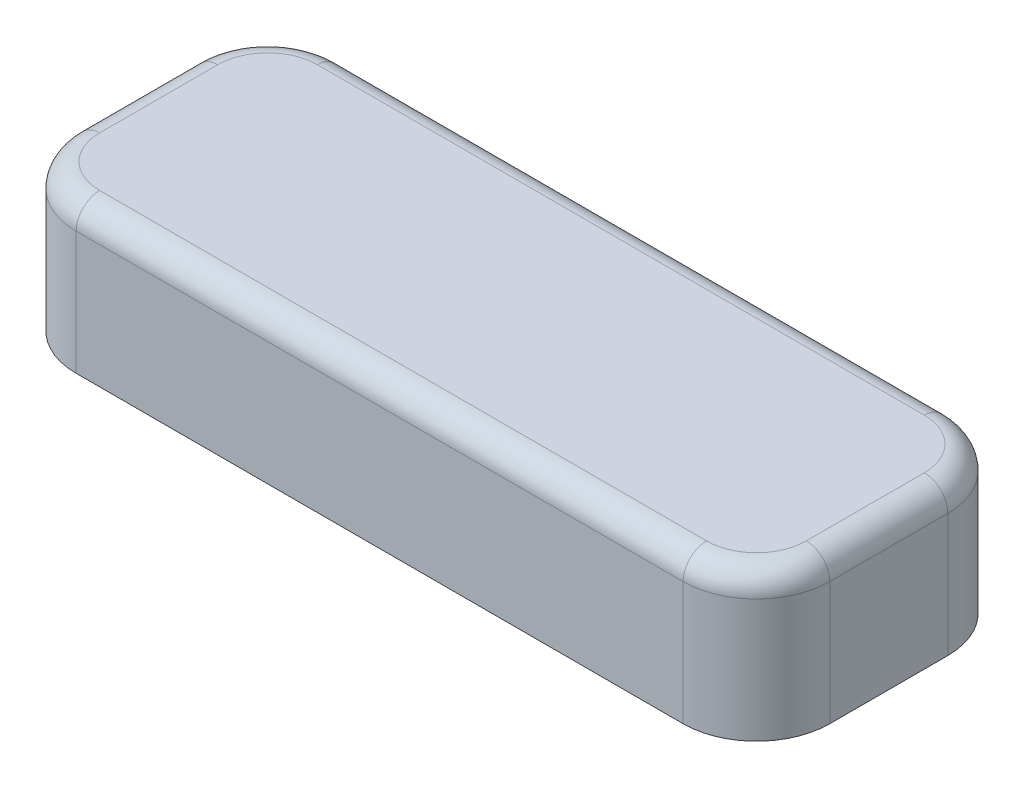
SolidWorks part; units mm, degrees
ref_plane "前视基准面" through (0, 0, 0) normal (0, 0, 1) x (1, 0, 0)
ref_plane "上视基准面" through (0, 0, 0) normal (0, 1, 0) x (1, 0, 0)
ref_plane "右视基准面" through (0, 0, 0) normal (1, 0, 0) x (0, 0, -1)
other "Configuration Table"
sketch "草图1" plane through (0, 0, 0) normal (0, 1, 0) x (1, 0, 0)
  line L0 (-2.2, 0) -> (2.2, 0) construction
  line L1 (0, 2.2) -> (0, -2.2) construction
  line L2 (2.2, 0.6) -> (2.2, -0.6)
  line L3 (-0.6, 2.2) -> (0.6, 2.2)
  line L4 (-2.2, -0.6) -> (-2.2, 0.6)
  line L5 (-0.6, -2.2) -> (0.6, -2.2)
  line L6 (-0.6, 2.2) -> (-0.6, 0.6)
  line L7 (-0.6, 0.6) -> (-2.2, 0.6)
  line L8 (-2.2, -0.6) -> (-0.6, -0.6)
  line L9 (-0.6, -0.6) -> (-0.6, -2.2)
  line L10 (0.6, -2.2) -> (0.6, -0.6)
  line L11 (0.6, -0.6) -> (2.2, -0.6)
  line L12 (2.2, 0.6) -> (0.6, 0.6)
  line L13 (0.6, 0.6) -> (0.6, 2.2)
  line L14 (-11.9062, 0) -> (11.9062, 0) construction
  line L15 (-14.1063, 0) -> (-9.7062, 0) construction
  line L16 (-11.9062, 2.2) -> (-11.9062, -2.2) construction
  line L17 (-14.1063, -0.6) -> (-14.1063, 0.6)
  line L18 (-12.5062, -2.2) -> (-11.3063, -2.2)
  line L19 (-11.3063, 2.2) -> (-12.5062, 2.2)
  line L20 (-9.7062, -0.6) -> (-9.7062, 0.6)
  line L21 (-14.1063, -0.6) -> (-12.5062, -0.6)
  line L22 (-12.5062, -0.6) -> (-12.5062, -2.2)
  line L23 (-11.3063, -2.2) -> (-11.3063, -0.6)
  line L24 (-11.3063, -0.6) -> (-9.7062, -0.6)
  line L25 (-9.7062, 0.6) -> (-11.3063, 0.6)
  line L26 (-11.3063, 0.6) -> (-11.3063, 2.2)
  line L27 (-12.5062, 2.2) -> (-12.5062, 0.6)
  line L28 (-12.5062, 0.6) -> (-14.1063, 0.6)
  line L29 (9.7062, 0) -> (14.1063, 0) construction
  line L30 (11.9062, -2.2) -> (11.9062, 2.2) construction
  line L31 (9.7062, 0.6) -> (9.7062, -0.6)
  line L32 (11.3063, 2.2) -> (12.5062, 2.2)
  line L33 (14.1063, -0.6) -> (14.1063, 0.6)
  line L34 (11.3063, -2.2) -> (12.5062, -2.2)
  line L35 (9.7062, 0.6) -> (11.3063, 0.6)
  line L36 (11.3063, 0.6) -> (11.3063, 2.2)
  line L37 (12.5062, 2.2) -> (12.5062, 0.6)
  line L38 (12.5062, 0.6) -> (14.1063, 0.6)
  line L39 (14.1063, -0.6) -> (12.5062, -0.6)
  line L40 (12.5062, -0.6) -> (12.5062, -2.2)
  line L41 (11.3063, -2.2) -> (11.3063, -0.6)
  line L42 (11.3063, -0.6) -> (9.7062, -0.6)
  circle A0 centre (0, 0) radius 2.8
  circle A1 centre (-11.9062, 0) radius 2.8
  circle A2 centre (11.9062, 0) radius 2.8
  point P4 (0, 0)
  point P7 (0, 0)
  point P10 (2.2, 0)
  point P13 (0, 2.2)
  point P16 (-2.2, 0)
  point P19 (0, -2.2)
  point P28 (0, 0)
  point P31 (-11.9062, 0)
  point P34 (-11.9062, 0)
  point P37 (-14.1063, 0)
  point P40 (-11.9062, -2.2)
  point P43 (-11.9062, 2.2)
  point P46 (-9.7062, 0)
  point P54 (11.9062, 0)
  point P57 (11.9062, 0)
  point P60 (9.7062, 0)
  point P63 (11.9062, 2.2)
  point P66 (14.1063, 0)
  point P69 (11.9062, -2.2)
  dimension "D7" = 5.6
  dimension "D15" = 5.6
  dimension "D22" = 5.6
  dimension "D1" = 4.4
  dimension "D2" = 4.4
  dimension "D3" = 1.2
  dimension "D4" = 1.2
  dimension "D5" = 1.2
  dimension "D6" = 1.2
  dimension "D8" = 23.8125
  dimension "D9" = 4.4
  dimension "D10" = 4.4
  dimension "D11" = 1.2
  dimension "D12" = 1.2
  dimension "D13" = 1.2
  dimension "D14" = 1.2
  dimension "D16" = 4.4
  dimension "D17" = 4.4
  dimension "D18" = 1.2
  dimension "D19" = 1.2
  dimension "D20" = 1.2
  dimension "D21" = 1.2
extrude "凸台-拉伸1" add sketch "草图1" against normal blind 8
sketch "草图2" plane through (0, 0, 0) normal (0, 1, 0) x (1, 0, 0)
  line L0 (0, -9.025) -> (0, 9.025) construction
  line L1 (-25.6938, 9.025) -> (25.6938, 9.025)
  line L2 (-25.6938, -9.025) -> (25.6938, -9.025)
  line L3 (-25.6938, 9.025) -> (-25.6938, -9.025)
  line L4 (25.6938, 9.025) -> (25.6938, -9.025)
  point P4 (0, 0)
  point P8 (0, 9.025)
  point P11 (0, -9.025)
  dimension "D1" = 18.05
  dimension "D2" = 51.3875
extrude "凸台-拉伸2" add sketch "草图2" along normal blind 1
sketch "草图3" plane through (0, 0, 0) normal (0, 1, 0) x (1, 0, 0)
  line L4 (25.6938, -9.025) -> (25.6938, 9.025)
  line L5 (-25.6938, -9.025) -> (25.6938, -9.025)
  line L6 (-25.6938, 9.025) -> (-25.6938, -9.025)
  line L7 (25.6938, 9.025) -> (-25.6938, 9.025)
  line L8 (25.6938, -9.025) -> (25.6938, 9.025)
  line L9 (-25.6938, -9.025) -> (25.6938, -9.025)
  line L10 (-25.6938, 9.025) -> (-25.6938, -9.025)
  line L11 (25.6938, 9.025) -> (-25.6938, 9.025)
  line L20 (24.6938, -8.025) -> (24.6938, 8.025)
  line L21 (24.6938, 8.025) -> (-24.6938, 8.025)
  line L22 (-24.6938, 8.025) -> (-24.6938, -8.025)
  line L23 (-24.6938, -8.025) -> (24.6938, -8.025)
  line L24 (24.6938, -8.025) -> (24.6938, 8.025)
  line L25 (24.6938, 8.025) -> (-24.6938, 8.025)
  line L26 (-24.6938, 8.025) -> (-24.6938, -8.025)
  line L27 (-24.6938, -8.025) -> (24.6938, -8.025)
  dimension "D1" = 0
  dimension "D2" = 1
extrude "凸台-拉伸3" add sketch "草图3" against normal blind 9
sketch "草图4" plane through (0, 0, 0) normal (0, 1, 0) x (1, 0, 0)
  line L0 (9.7062, 0.6) -> (9.7062, -0.6) construction
  line L1 (12.5062, 2.2) -> (11.3063, 2.2) construction
  line L2 (11.3063, -2.2) -> (12.5062, -2.2) construction
  line L3 (14.1063, -0.6) -> (14.1063, 0.6) construction
  line L4 (2.2, -0.6) -> (2.2, 0.6) construction
  line L5 (0.6, 2.2) -> (-0.6, 2.2) construction
  line L6 (-2.2, 0.6) -> (-2.2, -0.6) construction
  line L7 (-0.6, -2.2) -> (0.6, -2.2) construction
  line L8 (-11.3063, 2.2) -> (-12.5062, 2.2) construction
  line L9 (-9.7062, -0.6) -> (-9.7062, 0.6) construction
  line L10 (-12.5062, -2.2) -> (-11.3063, -2.2) construction
  line L11 (-14.1063, 0.6) -> (-14.1063, -0.6) construction
  line L12 (9.7062, 0.6) -> (9.7062, -0.6)
  line L13 (12.5062, 2.2) -> (11.3063, 2.2)
  line L14 (11.3063, -2.2) -> (12.5062, -2.2)
  line L15 (14.1063, -0.6) -> (14.1063, 0.6)
  line L16 (2.2, -0.6) -> (2.2, 0.6)
  line L17 (0.6, 2.2) -> (-0.6, 2.2)
  line L18 (-2.2, 0.6) -> (-2.2, -0.6)
  line L19 (-0.6, -2.2) -> (0.6, -2.2)
  line L20 (-11.3063, 2.2) -> (-12.5062, 2.2)
  line L21 (-9.7062, -0.6) -> (-9.7062, 0.6)
  line L22 (-12.5062, -2.2) -> (-11.3063, -2.2)
  line L23 (-14.1063, 0.6) -> (-14.1063, -0.6)
  line L24 (-14.1063, -0.6) -> (-24.6938, -0.6)
  line L25 (-24.6938, 8.025) -> (-24.6938, -8.025) construction
  line L26 (-24.6938, -0.6) -> (-24.6938, 0.6)
  line L27 (-24.6938, 8.025) -> (-24.6938, -8.025) construction
  line L28 (-24.6938, 0.6) -> (-14.1063, 0.6)
  line L29 (-12.5062, -2.2) -> (-12.5062, -8.025)
  line L30 (-24.6938, -8.025) -> (24.6938, -8.025) construction
  line L31 (-12.5062, -8.025) -> (-11.3063, -8.025)
  line L32 (-24.6938, -8.025) -> (24.6938, -8.025) construction
  line L33 (-11.3063, -8.025) -> (-11.3063, -2.2)
  line L34 (-12.5062, 2.2) -> (-12.5062, 8.025)
  line L35 (24.6938, 8.025) -> (-24.6938, 8.025) construction
  line L36 (-12.5062, 8.025) -> (-11.3063, 8.025)
  line L37 (24.6938, 8.025) -> (-24.6938, 8.025) construction
  line L38 (-11.3063, 8.025) -> (-11.3063, 2.2)
  line L39 (-9.7062, -0.6) -> (-2.2, -0.6)
  line L40 (-2.2, 0.6) -> (-9.7062, 0.6)
  line L41 (-0.6, -2.2) -> (-0.6, -8.025)
  line L42 (-0.6, -8.025) -> (0.6, -8.025)
  line L43 (0.6, -8.025) -> (0.6, -2.2)
  line L44 (2.2, -0.6) -> (9.7062, -0.6)
  line L45 (9.7062, 0.6) -> (2.2, 0.6)
  line L46 (0.6, 2.2) -> (0.6, 8.025)
  line L47 (0.6, 8.025) -> (-0.6, 8.025)
  line L48 (-0.6, 8.025) -> (-0.6, 2.2)
  line L49 (11.3063, -2.2) -> (11.3063, -8.025)
  line L50 (11.3063, -8.025) -> (12.5062, -8.025)
  line L51 (12.5062, -8.025) -> (12.5062, -2.2)
  line L52 (14.1063, -0.6) -> (24.6938, -0.6)
  line L53 (24.6938, -8.025) -> (24.6938, 8.025) construction
  line L54 (24.6938, -0.6) -> (24.6938, 0.6)
  line L55 (24.6938, 0.6) -> (14.1063, 0.6)
  line L56 (12.5062, 2.2) -> (12.5062, 8.025)
  line L57 (12.5062, 8.025) -> (11.3062, 8.025)
  line L58 (11.3062, 8.025) -> (11.3063, 2.2)
extrude "凸台-拉伸4" add sketch "草图4" against normal blind 2.5
fillet "圆角1" radius 5 8 edges at (-25.6938, -4, -9.025) (25.6938, -4, -9.025) (25.6938, -4, 9.025) (-25.6938, -4, 9.025) (-24.6938, -4.5, -8.025) (24.6938, -4.5, -8.025) (24.6938, -4.5, 8.025) (-24.6938, -4.5, 8.025)
fillet "圆角2" radius 1.6 24 edges at (24.6938, 0, 1.8125) (16.1, 0, 8.025) (16.1, 0, -8.025) (24.6938, 0, -1.8125) (-24.6938, 0, -1.8125) (-16.1, 0, -8.025) (-16.1, 0, 8.025) (-24.6938, 0, 1.8125) (24.2293, 1, -7.5605) (25.6938, 1, 0) (24.2293, 1, 7.5605) (0, 1, 9.025) (-24.2293, 1, 7.5605) (-25.6938, 1, 0) (-24.2293, 1, -7.5605) (0, 1, -9.025) (5.9531, 0, -8.025) (-5.9531, 0, -8.025) (-5.9531, 0, 8.025) (5.9531, 0, 8.025) (23.2293, 0, 6.5605) (23.2293, 0, -6.5605) (-23.2293, 0, -6.5605) (-23.2293, 0, 6.5605)
